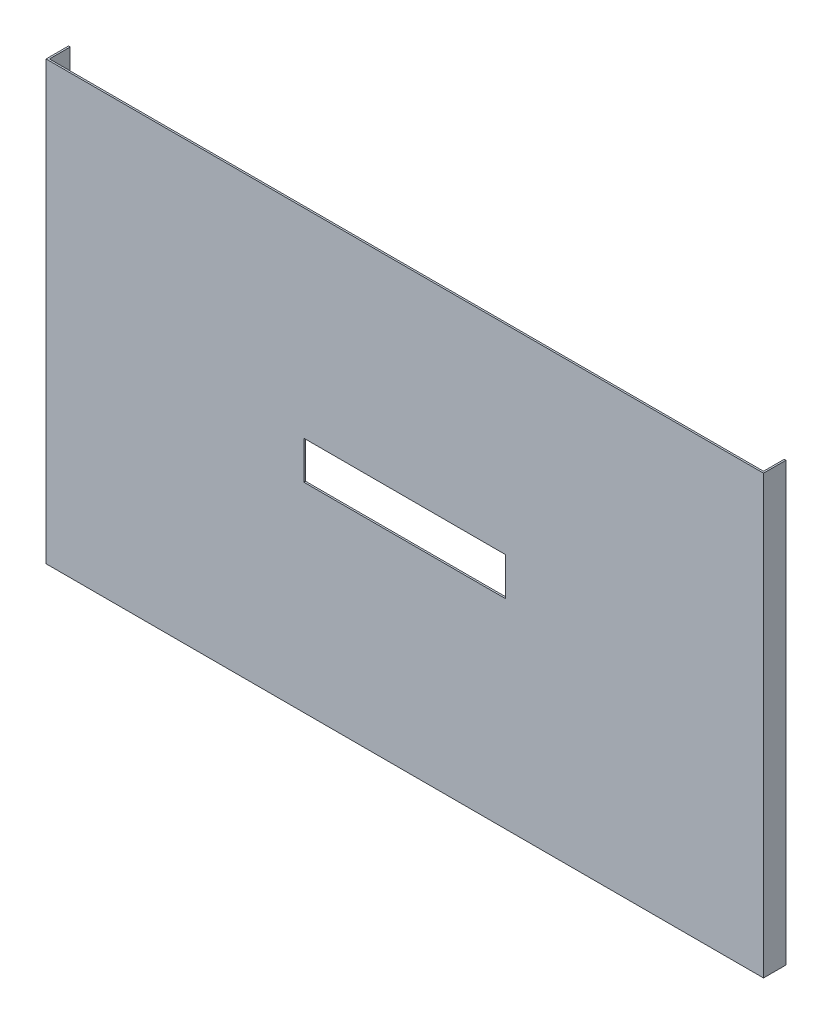
SolidWorks part; units mm, degrees
ref_plane "Front Plane" through (0, 0, 0) normal (0, 0, 1) x (1, 0, 0)
ref_plane "Top Plane" through (0, 0, 0) normal (0, 1, 0) x (1, 0, 0)
ref_plane "Right Plane" through (0, 0, 0) normal (1, 0, 0) x (0, 0, -1)
other "Configuration Table"
sketch "Sketch1" plane through (0, 0, 0) normal (0, 1, 0) x (1, 0, 0)
  line L0 (30, -40) -> (30, -20)
  line L1 (30, -20) -> (31.5, -20)
  line L2 (31.5, -20) -> (31.5, -38.5)
  line L3 (31.5, -38.5) -> (668.5, -38.5)
  line L4 (668.5, -38.5) -> (668.5, -20)
  line L5 (668.5, -20) -> (670, -20)
  line L6 (670, -20) -> (670, -40)
  line L7 (670, -40) -> (30, -40)
extrude "TOPPING_klape_kat1_kapak_1" add sketch "Sketch1" along normal blind 390 from offset 1560 separate body
sketch "Sketch2" plane through (0, 0, 0) normal (0, 0, 1) x (1, 0, 0)
  line L1 (260, 1738) -> (440, 1738)
  line L2 (260, 1738) -> (260, 1772)
  line L3 (260, 1772) -> (440, 1772)
  line L4 (440, 1738) -> (440, 1772)
extrude "TOPPING_klape_kat1_kapak_2" cut sketch "Sketch2" along normal blind 14 from offset 27
